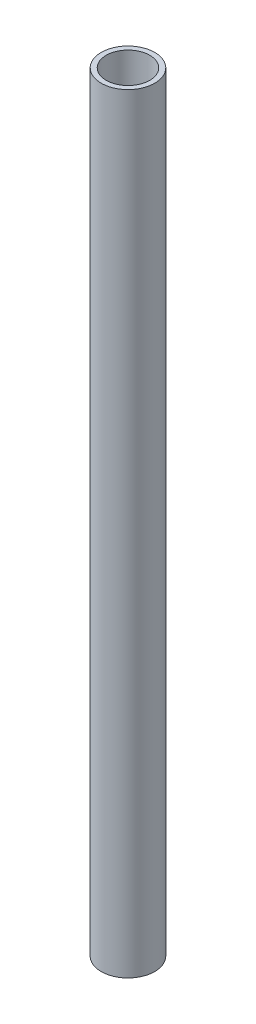
SolidWorks part; units mm, degrees
material "AISI 4130 Steel, annealed at 865C"
ref_plane "X-Y Datum" through (0, 0, 0) normal (0, 0, 1) x (1, 0, 0)
ref_plane "X-Z Datum" through (0, 0, 0) normal (0, 1, 0) x (1, 0, 0)
ref_plane "Y-Z Datum" through (0, 0, 0) normal (1, 0, 0) x (0, 0, -1)
sketch "Sketch1" plane through (0, 0, 0) normal (0, 1, 0) x (1, 0, 0)
  circle A0 centre (0, 0) radius 7.9375
  circle A1 centre (0, 0) radius 6.4643
  dimension "D1" = 1.4732
  dimension "D2" = 15.875
extrude "Boss-Extrude1" add sketch "Sketch1" along normal offset from surface (228.427 mm away) 25.4
sketch "Sketch2" plane through (0, 0, 0) normal (1, 0, 0) x (0, 0, -1)
  line L0 (-3.175, 228.427) -> (-3.175, 203.027)
  line L1 (6.4643, 228.427) -> (-6.4643, 228.427) construction
  line L2 (3.175, 203.027) -> (3.175, 228.427)
  line L3 (3.175, 228.427) -> (-3.175, 228.427)
  line L5 (7.9375, 0) -> (7.9375, 228.427) construction
  arc A0 (-3.175, 203.027) -> (3.175, 203.027) centre (0, 203.027) ccw
  dimension "D1" = 6.35
  dimension "D2" = 25.4
  dimension "D3" = 4.7625
